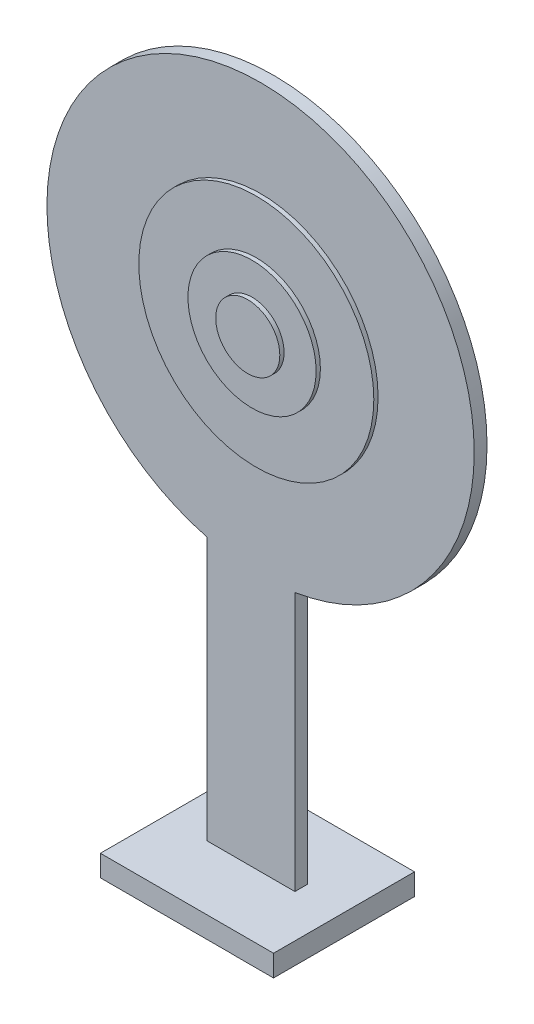
SolidWorks part; units mm, degrees
ref_plane "前视基准面" through (0, 0, 0) normal (0, 0, 1) x (1, 0, 0)
ref_plane "上视基准面" through (0, 0, 0) normal (0, 1, 0) x (1, 0, 0)
ref_plane "右视基准面" through (0, 0, 0) normal (1, 0, 0) x (0, 0, -1)
sketch "草图2" plane through (0, 0, 0) normal (0, 0, 1) x (1, 0, 0)
  circle A0 centre (0, 0) radius 50
  dimension "D1" = 100
extrude "凸台-拉伸1" add sketch "草图2" along normal blind 3
sketch "草图3" plane through (0, 0, 3) normal (0, 0, 1) x (1, 0, 0)
  circle A0 centre (0, 0) radius 27.5
  dimension "D1" = 55
extrude "凸台-拉伸2" add sketch "草图3" along normal blind 1
sketch "草图4" plane through (0, 0, 4) normal (0, 0, 1) x (1, 0, 0)
  circle A0 centre (0, 0) radius 15
  dimension "D1" = 30
extrude "凸台-拉伸3" add sketch "草图4" along normal blind 1
sketch "草图5" plane through (0, 0, 5) normal (0, 0, 1) x (1, 0, 0)
  circle A0 centre (0, 0) radius 7.5
  dimension "D1" = 15
extrude "凸台-拉伸4" add sketch "草图5" along normal blind 1
sketch "草图6" plane through (0, 0, 0) normal (0, 0, 1) x (1, 0, 0)
  line L0 (-12.4911, -48.4146) -> (-12.4911, -114.9646)
  line L1 (-12.4911, -114.9646) -> (8.0281, -114.9646)
  line L2 (8.0281, -114.9646) -> (8.0281, -49.3513)
  circle A0 centre (0, 0) radius 50 construction
  circle A2 centre (0, 0) radius 50
  arc A3 (-12.4911, -48.4146) -> (8.0281, -49.3513) centre (0, 0) ccw
  dimension "D2" = 66.55
  dimension "D1" = 0
extrude "凸台-拉伸5" add sketch "草图6" along normal blind 3
sketch "草图16" plane through (8.0281, 0, 0) normal (1, 0, 0) x (0, 0, -1)
  line L0 (0, -114.9646) -> (0, -109.9646)
  line L1 (0, -114.9646) -> (15, -114.9646)
  line L2 (0, -109.9646) -> (15, -109.9646)
  line L3 (15, -114.9646) -> (15, -109.9646)
  line L4 (0, -114.9646) -> (0, -49.3513) construction
  dimension "D1" = 5
  dimension "D2" = 15
extrude "凸台-拉伸7" add sketch "草图16" against normal blind 20.52
sketch "草图18" plane through (8.0281, 0, 0) normal (1, 0, 0) x (0, 0, -1)
  line L0 (-3, -114.9646) -> (-3, -109.9646)
  line L1 (-3, -114.9646) -> (-18, -114.9646)
  line L2 (-3, -109.9646) -> (-18, -109.9646)
  line L3 (-18, -114.9646) -> (-18, -109.9646)
  line L4 (-3, -114.9646) -> (-3, -49.3513) construction
  dimension "D1" = 15
  dimension "D2" = 5
extrude "凸台-拉伸9" add sketch "草图18" against normal blind 20.55
sketch "草图19" plane through (8.0281, 0, 0) normal (1, 0, 0) x (0, 0, -1)
  line L0 (-18, -109.9646) -> (15, -109.9646)
  line L1 (-18, -109.9646) -> (-18, -114.9876)
  line L2 (15, -109.9646) -> (15, -114.9876)
  line L3 (-18, -114.9876) -> (15, -114.9876)
extrude "凸台-拉伸10" add sketch "草图19" along normal blind 10
sketch "草图20" plane through (-12.4919, 0, 0) normal (-1, 0, 0) x (0, 0, 1)
  line L0 (-15, -109.9646) -> (18, -109.9646)
  line L1 (-15, -109.9646) -> (-15, -114.9487)
  line L2 (18, -109.9646) -> (18, -114.9487)
  line L3 (-15, -114.9487) -> (18, -114.9487)
extrude "凸台-拉伸11" add sketch "草图20" along normal blind 10
